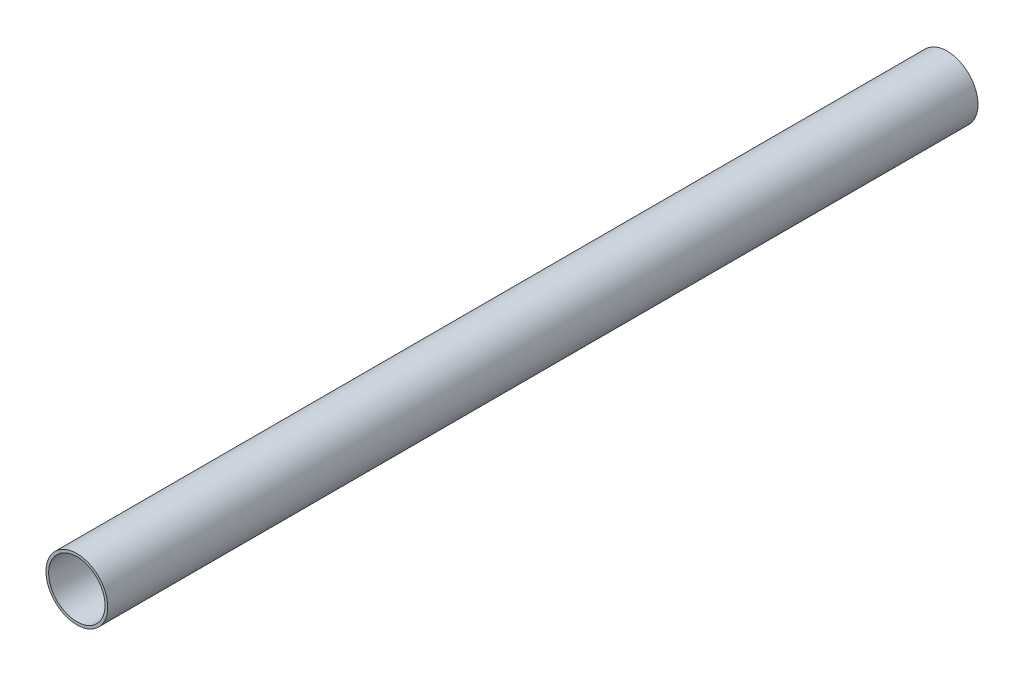
SolidWorks part; units mm, degrees
material "Wildman Fiberglass"
ref_plane "Front Plane" through (0, 0, 0) normal (0, 0, 1) x (1, 0, 0)
ref_plane "Top Plane" through (0, 0, 0) normal (0, 1, 0) x (1, 0, 0)
ref_plane "Right Plane" through (0, 0, 0) normal (1, 0, 0) x (0, 0, -1)
sketch "Sketch1" plane through (0, 0, 0) normal (0, 0, 1) x (1, 0, 0)
  circle A0 centre (0, 0) radius 15.9385
  circle A1 centre (0, 0) radius 14.5415
  dimension "D1" = 31.877
  dimension "D2" = 29.083
extrude "Boss-Extrude1" add sketch "Sketch1" along normal blind 448.945
